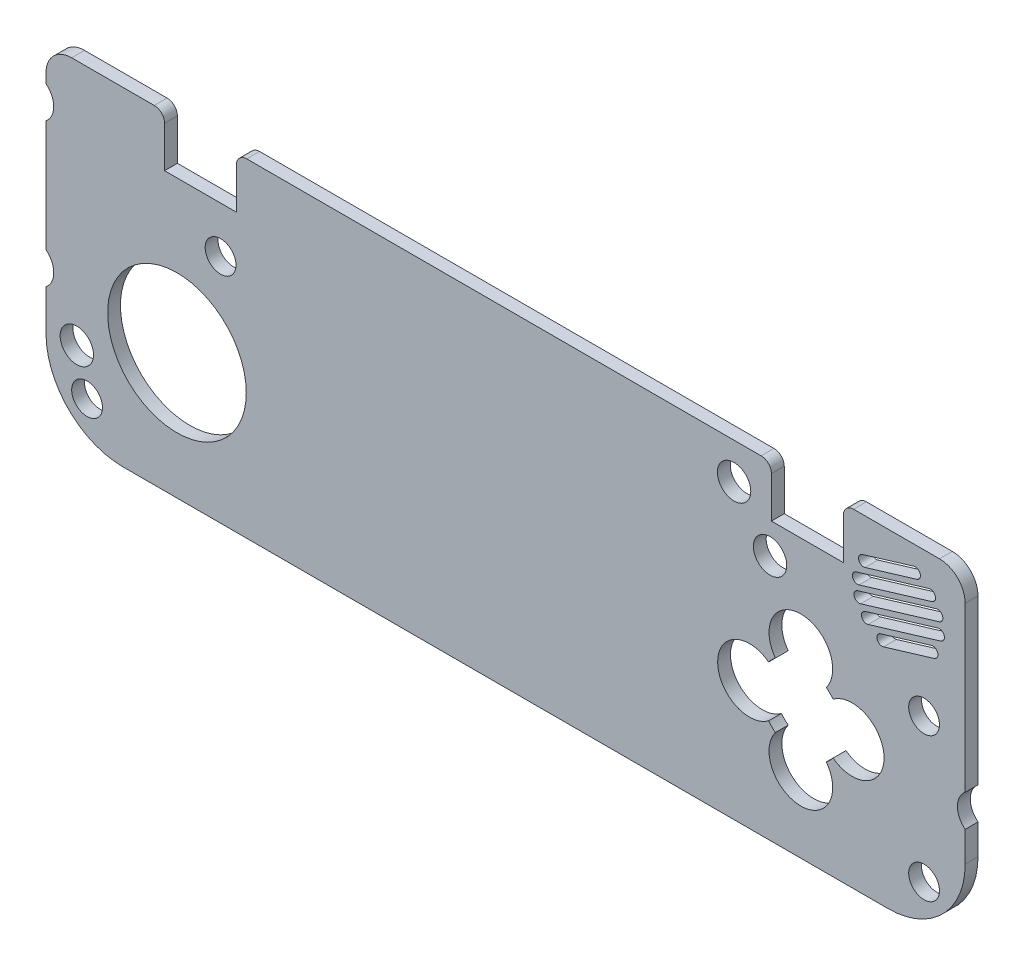
SolidWorks part; units mm, degrees
ref_plane "Plan de face" through (0, 0, 0) normal (0, 0, 1) x (1, 0, 0)
ref_plane "Plan de dessus" through (0, 0, 0) normal (0, 1, 0) x (1, 0, 0)
ref_plane "Plan de droite" through (0, 0, 0) normal (1, 0, 0) x (0, 0, -1)
sketch "Esquisse1" plane through (0, 0, 0) normal (0, 0, 1) x (1, 0, 0)
  line L1 (-89.2039, 33.3448) -> (79.7961, 33.3448)
  line L2 (-94.2039, 28.3448) -> (-94.2039, -15.6552)
  line L3 (-79.2039, -30.6552) -> (69.7961, -30.6552)
  line L4 (84.7961, 28.3448) -> (84.7961, -15.6552)
  arc A0 (-89.2039, 33.3448) -> (-94.2039, 28.3448) centre (-89.2039, 28.3448) ccw
  arc A1 (79.7961, 33.3448) -> (84.7961, 28.3448) centre (79.7961, 28.3448) cw
  arc A2 (69.7961, -30.6552) -> (84.7961, -15.6552) centre (69.7961, -15.6552) ccw
  arc A3 (-94.2039, -15.6552) -> (-79.2039, -30.6552) centre (-79.2039, -15.6552) ccw
  point P6 (-94.2039, 33.3448)
  point P9 (84.7961, 33.3448)
  point P12 (84.7961, -30.6552)
  dimension "D3" = 5
  dimension "D4" = 5
  dimension "D5" = 15
  dimension "D6" = 15
  dimension "D1" = 179
  dimension "D2" = 64
extrude "Boss.-Extru.1" add sketch "Esquisse1" along normal blind 2.5 contours L1 A1 L4 A2 L3 A3 L2 A0
sketch "12x12 Button" plane through (0, 0, 2.5) normal (0, 0, 1) x (1, 0, 0)
  line L0 (84.7961, 28.3448) -> (84.7961, -15.6552) construction
  line L1 (-79.2039, -30.6552) -> (69.7961, -30.6552) construction
  circle A0 centre (42.7961, -5.6552) radius 6.2
  circle A1 centre (52.7961, 4.3448) radius 6.2
  circle A2 centre (52.7961, -15.6552) radius 6.2
  circle A3 centre (62.7961, -5.6552) radius 6.2
  arc A5 (46.5181, -0.6967) -> (47.8376, 0.6228) centre (52.7961, -5.6552) cw
  arc A6 (59.0741, -0.6967) -> (57.7546, 0.6228) centre (52.7961, -5.6552) ccw
  arc A7 (59.0741, -10.6137) -> (57.7546, -11.9332) centre (52.7961, -5.6552) cw
  arc A9 (46.5181, -10.6137) -> (47.8376, -11.9332) centre (52.7961, -5.6552) ccw
  dimension "D1" = 22
  dimension "D2" = 32
  dimension "D3" = 42
  dimension "D4" = 32
  dimension "D5" = 15
  dimension "D6" = 35
  dimension "D7" = 25
  dimension "D8" = 25
sketch "Joystick" plane through (0, 0, 2.5) normal (0, 0, 1) x (1, 0, 0)
  line L0 (-79.2039, -30.6552) -> (69.7961, -30.6552) construction
  line L1 (-94.2039, 28.3448) -> (-94.2039, -15.6552) construction
  circle A0 centre (-68.7039, -6.1552) radius 13.5
  dimension "D1" = 24.5
  dimension "D2" = 25.5
extrude "Enlèv. mat.-Extru.2" cut sketch "Joystick" against normal blind 2.5
sketch "Esquisse2" plane through (0, 0, 2.5) normal (0, 0, 1) x (1, 0, 0)
  line L0 (-89.2039, 33.3448) -> (79.7961, 33.3448) construction
  line L1 (47.0661, 33.3448) -> (61.0661, 33.3448)
  line L2 (47.0661, 33.3448) -> (47.0661, 23.3448)
  line L3 (47.0661, 23.3448) -> (61.0661, 23.3448)
  line L4 (61.0661, 33.3448) -> (61.0661, 23.3448)
  line L5 (84.7961, 28.3448) -> (84.7961, -15.6552) construction
  dimension "D1" = 23.73
  dimension "D2" = 14
extrude "Enlèv. mat.-Extru.3" cut sketch "Esquisse2" against normal blind 10
fillet "Congé1" radius 2 1 edges at (47.0661, 33.3448, 1.25)
fillet "Congé2" radius 2 1 edges at (61.0661, 33.3448, 1.25)
sketch "Esquisse3" plane through (0, 0, 2.5) normal (0, 0, 1) x (1, 0, 0)
  line L0 (-89.2039, 33.3448) -> (45.0661, 33.3448) construction
  line L1 (-71.1139, 33.3448) -> (-57.1139, 33.3448)
  line L2 (-71.1139, 33.3448) -> (-71.1139, 23.3448)
  line L3 (-71.1139, 23.3448) -> (-57.1139, 23.3448)
  line L4 (-57.1139, 33.3448) -> (-57.1139, 23.3448)
  line L5 (-94.2039, 28.3448) -> (-94.2039, -15.6552) construction
  dimension "D1" = 23.09
  dimension "D2" = 10
  dimension "D3" = 14
extrude "Enlèv. mat.-Extru.4" cut sketch "Esquisse3" against normal blind 10 contours L2 L1 L4 L3
fillet "Congé3" radius 2 1 edges at (-71.1139, 33.3448, 1.25)
fillet "Congé4" radius 2 1 edges at (-57.1139, 33.3448, 1.25)
extrude "Enlèv. mat.-Extru.5" cut sketch "12x12 Button" against normal blind 10 contours A0 A9 A2 A7 A3 A6 A1 A5 | A0 | A1 | A3 | A2
sketch "Esquisse4" plane through (0, 0, 2.5) normal (0, 0, 1) x (1, 0, 0)
  line L0 (84.7961, 28.3448) -> (84.7961, -15.6552) construction
  line L1 (64.137, 19.0344) -> (79.4552, 23.6552) construction
  line L2 (63.0661, 33.3448) -> (79.7961, 33.3448) construction
  line L3 (63.8482, 19.9918) -> (79.1664, 24.6126)
  line L4 (64.4258, 18.077) -> (79.744, 22.6978)
  line L5 (63.8286, 22.0649) -> (78.0363, 26.3507) construction
  line L6 (63.5398, 23.0223) -> (77.7475, 27.3081)
  line L7 (64.1174, 21.1075) -> (78.3251, 25.3933)
  line L8 (65.0217, 25.6002) -> (75.0872, 28.6364) construction
  line L9 (64.7329, 26.5575) -> (74.7984, 29.5938)
  line L10 (65.3105, 24.6428) -> (75.376, 27.6791)
  line L11 (65.6035, 16.28) -> (79.7564, 20.5493) construction
  line L12 (65.3147, 17.2374) -> (79.4676, 21.5066)
  line L13 (65.8923, 15.3226) -> (80.0452, 19.5919)
  line L14 (68.6116, 14.0059) -> (78.5077, 16.9911) construction
  line L15 (68.3228, 14.9633) -> (78.2189, 17.9485)
  line L16 (68.9004, 13.0485) -> (78.7965, 16.0337)
  circle A0 centre (71.7961, 21.3448) radius 10
  circle A1 centre (71.7961, 21.3448) radius 8
  arc A2 (63.8482, 19.9918) -> (64.4258, 18.077) centre (64.137, 19.0344) ccw
  arc A3 (79.744, 22.6978) -> (79.1664, 24.6126) centre (79.4552, 23.6552) ccw
  arc A4 (63.5398, 23.0223) -> (64.1174, 21.1075) centre (63.8286, 22.0649) ccw
  arc A5 (78.3251, 25.3933) -> (77.7475, 27.3081) centre (78.0363, 26.3507) ccw
  arc A6 (64.7329, 26.5575) -> (65.3105, 24.6428) centre (65.0217, 25.6002) ccw
  arc A7 (75.376, 27.6791) -> (74.7984, 29.5938) centre (75.0872, 28.6364) ccw
  arc A8 (65.3147, 17.2374) -> (65.8923, 15.3226) centre (65.6035, 16.28) ccw
  arc A9 (80.0452, 19.5919) -> (79.4676, 21.5066) centre (79.7564, 20.5493) ccw
  arc A10 (68.3228, 14.9633) -> (68.9004, 13.0485) centre (68.6116, 14.0059) ccw
  arc A11 (78.7965, 16.0337) -> (78.2189, 17.9485) centre (78.5077, 16.9911) ccw
  point P9 (71.7961, 21.3448)
  point P16 (70.9324, 24.2078)
  point P25 (70.0545, 27.1183)
  point P36 (72.68, 18.4146)
  point P47 (73.5596, 15.4985)
  dimension "D1" = 13
  dimension "D2" = 12
  dimension "D4" = 0
  dimension "D5" = 1.04
  dimension "D6" = 360
  dimension "D7" = 360
  dimension "D8" = 1.0459
extrude "Enlèv. mat.-Extru.8" cut sketch "Esquisse4" against normal blind 10 contours L4 A1 L3 | L3 A2 A0 L4 A1 | L6 A4 A0 A1 | L9 A6 A0 A1 | L10 A7 A1 L9 A6 | A1 A9 L12 A8 L13 | A1 A8 A0 L13 | A1 A10 A0 L16 | A1 A11 L15 A10 L16 | L16 A11 A0 A1 | A0 A9 A1 L13 | A0 A3 L3 A1 L4 | A0 A5 L6 A1 | L7 A5 A1 L6 A4 | A0 A7 L9 A1
sketch "Esquisse5" plane through (0, 0, 2.5) normal (0, 0, 1) x (1, 0, 0)
  line L0 (84.7961, 28.3448) -> (84.7961, -15.6552) construction
  line L1 (-79.2039, -30.6552) -> (69.7961, -30.6552) construction
  line L2 (-94.2039, 28.3448) -> (-94.2039, -15.6552) construction
  line L7 (63.0661, 33.3448) -> (79.7961, 33.3448) construction
  line L8 (-55.1139, 33.3448) -> (45.0661, 33.3448) construction
  circle A0 centre (76.7961, -22.6552) radius 3
  circle A1 centre (-86.2039, -22.6552) radius 3
  circle A2 centre (76.7961, 5.3448) radius 3
  circle A3 centre (-60.2039, 14.3448) radius 3
  circle A4 centre (-88.2039, -14.6552) radius 3.25
  circle A5 centre (39.7961, 26.3448) radius 3.25
  circle A6 centre (46.7961, 17.3448) radius 3.25
  dimension "D1" = 8
  dimension "D3" = 8
  dimension "D5" = 8
  dimension "D7" = 19
  dimension "D9" = 6
  dimension "D11" = 7
  dimension "D13" = 38
  dimension "D2" = 8
  dimension "D4" = 8
  dimension "D6" = 28
  dimension "D8" = 34
  dimension "D10" = 16
  dimension "D12" = 45
  dimension "D14" = 16
extrude "Enlèv. mat.-Extru.9" cut sketch "Esquisse5" against normal blind 10
sketch "Esquisse6" plane through (0, 0, 2.5) normal (0, 0, 1) x (1, 0, 0)
  line L0 (-76.1808, -30.6552) -> (-76.1808, -4.6552)
  line L1 (-79.2039, -30.6552) -> (69.7961, -30.6552) construction
  line L2 (-76.1808, -4.6552) -> (-94.2039, -4.6552)
  line L3 (-94.2039, 28.3448) -> (-94.2039, -15.6552) construction
  line L4 (-94.2039, -4.6552) -> (-99.2039, -4.6552)
  line L5 (-81.1589, 33.3448) -> (-81.1589, 23.3448)
  line L6 (-89.2039, 33.3448) -> (-73.1139, 33.3448) construction
  line L7 (-81.1589, 23.3448) -> (-94.2039, 23.3448)
  line L8 (-94.2039, 23.3448) -> (-99.2039, 23.3448)
  line L9 (68.4263, -30.6552) -> (68.4263, -6.6552)
  line L10 (68.4263, -6.6552) -> (84.7961, -6.6552)
  line L11 (84.7961, 28.3448) -> (84.7961, -15.6552) construction
  line L12 (84.7961, -6.6552) -> (89.7961, -6.6552)
  circle A0 centre (-96.7039, -4.6552) radius 4
  circle A1 centre (-96.7039, 23.3448) radius 4
  circle A2 centre (87.2961, -6.6552) radius 4
extrude "Enlèv. mat.-Extru.11" cut sketch "Esquisse6" against normal blind 10
